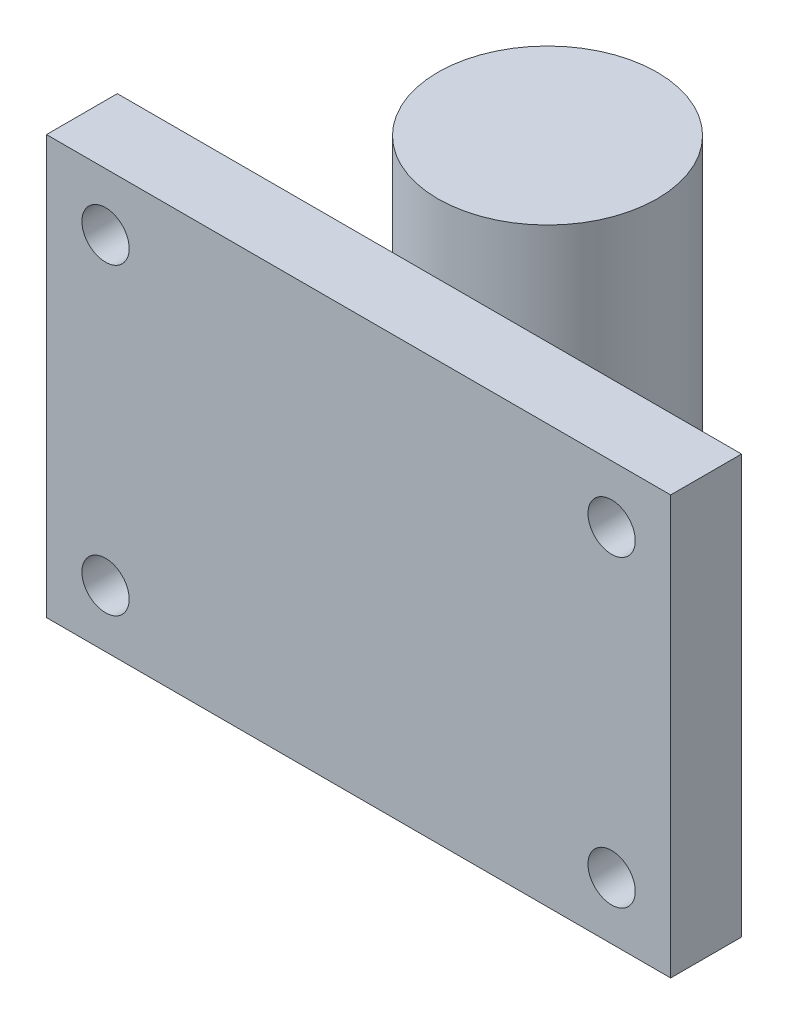
SolidWorks part; units mm, degrees
ref_plane "前视基准面" through (0, 0, 0) normal (0, 0, 1) x (1, 0, 0)
ref_plane "上视基准面" through (0, 0, 0) normal (0, 1, 0) x (1, 0, 0)
ref_plane "右视基准面" through (0, 0, 0) normal (1, 0, 0) x (0, 0, -1)
sketch "草图1" plane through (0, 0, 0) normal (0, 0, 1) x (1, 0, 0)
  line L1 (-92.5, -62) -> (92.5, -62)
  line L2 (-92.5, -62) -> (-92.5, 62)
  line L3 (-92.5, 62) -> (92.5, 62)
  line L4 (92.5, -62) -> (92.5, 62)
  line L5 (-92.5, -62) -> (92.5, 62) construction
  line L6 (-92.5, 62) -> (92.5, -62) construction
  point P0 (0, 0)
  dimension "D1" = 124
  dimension "D2" = 185
extrude "凸台-拉伸1" add sketch "草图1" along normal blind 21
sketch "草图3" plane through (0, 0, 0) normal (0, 1, 0) x (1, 0, 0)
  line L0 (92.5, 0) -> (-92.5, 0) construction
  line L1 (40, 0) -> (-40, 0)
  arc A0 (19.835, 37.5635) -> (40, 0) centre (79.1953, 45.2352) ccw
  arc A1 (-19.835, 37.5635) -> (-40, 0) centre (-79.1953, 45.2352) cw
  arc A2 (-19.835, 37.5635) -> (19.835, 37.5635) centre (0, 35) ccw
  point P3 (8.6605, 16.0319)
  point P4 (19.0803, 0)
  point P11 (8.5695, 13.9504)
  point P12 (-11.7258, 17.2511)
  point P13 (7.9836, 15.3769)
  point P14 (-13.5419, 15.5254)
  point P15 (-20.5525, 5.5541)
  point P16 (-20.1498, 0)
  point P17 (0, 0)
  point P18 (-13.4509, 13.9347)
  point P19 (0, 0)
  point P21 (12.287, 17.6353)
  point P22 (0, 0)
  point P23 (0, 28.3127)
  point P24 (31.6261, 25.9575)
  point P25 (0, 18.0846)
  point P26 (0, 28.7326)
  point P27 (0, 0)
  dimension "D2" = 20
  dimension "D1" = 80
  dimension "D3" = 35
  dimension "D4" = 20.165
extrude "凸台-拉伸2" add sketch "草图3" along normal mid plane 30
sketch "草图5" plane through (0, 0, 0) normal (0, 1, 0) x (1, 0, 0)
  arc A0 (-19.835, 37.5635) -> (19.835, 37.5635) centre (0, 35) ccw construction
  arc A1 (-19.835, 37.5635) -> (19.835, 37.5635) centre (0, 35) ccw construction
  circle A2 centre (0, 35) radius 32.5
  dimension "D1" = 65
extrude "凸台-拉伸3" add sketch "草图5" along normal mid plane 160
sketch "草图6" plane through (0, 0, 0) normal (0, 0, -1) x (-1, 0, 0)
  line L0 (-75, 45) -> (-75, -45) construction
  line L1 (-75, -45) -> (75, -45) construction
  line L2 (75, -45) -> (75, 45) construction
  line L3 (75, 45) -> (-75, 45) construction
  line L4 (-92.5, 62) -> (92.5, 62) construction
  line L5 (92.5, 62) -> (92.5, -62) construction
  circle A0 centre (-75, 45) radius 7
  circle A1 centre (75, 45) radius 7
  circle A2 centre (75, -45) radius 7
  circle A3 centre (-75, -45) radius 7
  point P8 (0, 45)
  point P11 (0, 62)
  point P14 (92.5, 0)
  point P15 (75, 0)
  dimension "D3" = 14
  dimension "D1" = 150
  dimension "D2" = 90
extrude "切除-拉伸1" cut sketch "草图6" against normal through all
